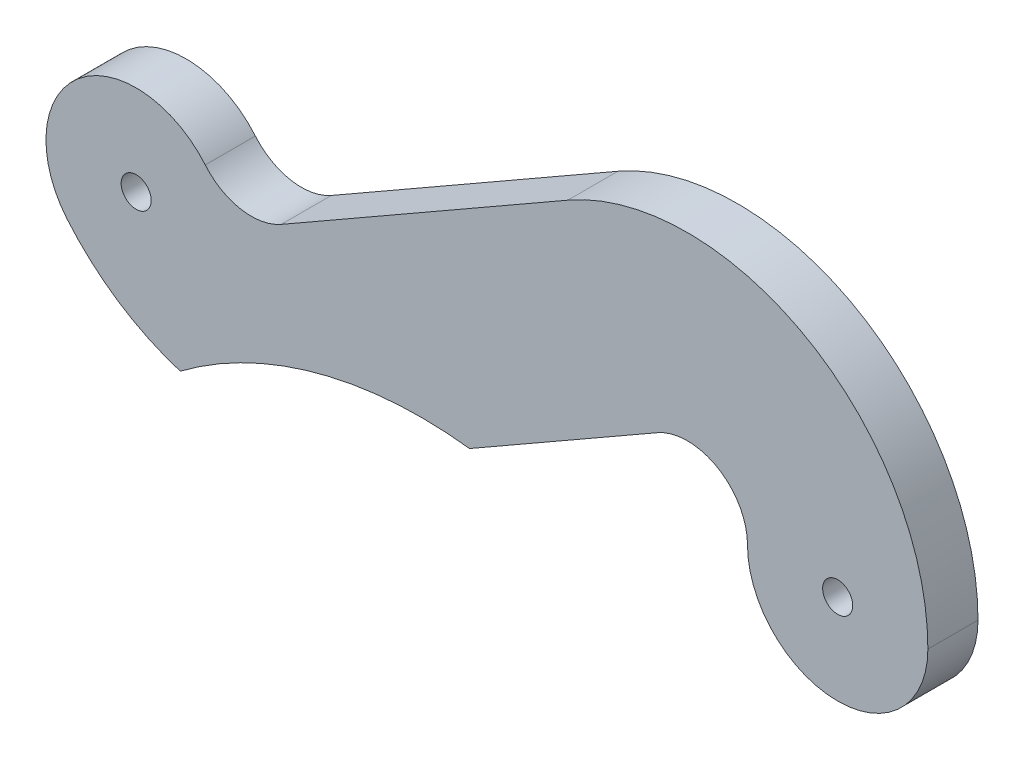
SolidWorks part; units mm, degrees
ref_plane "Plan de face" through (0, 0, 0) normal (0, 0, 1) x (1, 0, 0)
ref_plane "Plan de dessus" through (0, 0, 0) normal (0, 1, 0) x (1, 0, 0)
ref_plane "Plan de droite" through (0, 0, 0) normal (1, 0, 0) x (0, 0, -1)
sketch "Esquisse1" plane through (0, 0, 0) normal (0, 0, 1) x (1, 0, 0)
  line L0 (0, 0) -> (70, 0) construction
  line L1 (0, 0) -> (0, 15) construction
  line L2 (0, 0) -> (11.4907, 9.6418) construction
  line L3 (70, -15) -> (70, 0) construction
  line L4 (70, 0) -> (55, 0) construction
  line L5 (14.4741, 4.4361) -> (43.0662, 20.8227)
  line L6 (23.4245, -11.1809) -> (52.0166, 5.2057)
  arc A0 (11.4907, 9.6418) -> (0, 15) centre (0, 0) ccw construction
  arc A1 (16.0869, 13.4985) -> (0, 21) centre (0, 0) ccw construction
  circle A2 centre (70, 0) radius 1.5
  circle A3 centre (0, 0) radius 1.5
  arc A4 (6.8944, 5.7851) -> (0, 9) centre (0, 0) ccw construction
  arc A5 (6.8944, 5.7851) -> (16.0869, 13.4985) centre (11.4907, 9.6418) ccw construction
  arc A6 (0, 21) -> (0, 9) centre (0, 15) ccw construction
  arc A7 (55, 0) -> (70, -15) centre (70, 0) ccw construction
  arc A8 (49, 0) -> (70, -21) centre (70, 0) ccw construction
  arc A9 (61, 0) -> (70, -9) centre (70, 0) ccw construction
  arc A10 (61, 0) -> (49, 0) centre (55, 0) ccw construction
  arc A11 (70, -21) -> (70, -9) centre (70, -15) ccw construction
  arc A12 (6.8944, 5.7851) -> (-6.8944, -5.7851) centre (0, 0) ccw
  arc A13 (61, 0) -> (79, 0) centre (70, 0) ccw
  arc A14 (6.8944, 5.7851) -> (14.4741, 4.4361) centre (11.4907, 9.6418) ccw
  arc A15 (61, 0) -> (52.0166, 5.2057) centre (55, 0) ccw
  arc A16 (-6.8944, -5.7851) -> (23.4245, -11.1809) centre (11.4907, 9.6418) ccw
  arc A17 (79, 0) -> (43.0662, 20.8227) centre (55, 0) ccw
  point P6 (6.3393, 13.5946)
  point P15 (59.3934, -10.6066)
  dimension "D1" = 3
  dimension "D2" = 70
  dimension "D3" = 15
  dimension "D6" = 50
  dimension "D7" = 90
  dimension "D8" = 6
  dimension "D4" = 90
extrude "Boss.-Extru.1" add sketch "Esquisse1" along normal blind 5
sketch "Esquisse2" plane through (0, 0, 5) normal (0, 0, 1) x (1, 0, 0)
  line L1 (23.4245, -11.1809) -> (52.0166, 5.2057) construction
  arc A0 (4.4015, -13.2873) -> (33.2657, -5.5407) centre (28.4513, -45.2499) cw
  arc A1 (-6.8944, -5.7851) -> (23.4245, -11.1809) centre (11.4907, 9.6418) ccw construction
  arc A2 (4.4015, -13.2873) -> (33.2657, -5.5407) centre (13.6384, 9.9437) ccw
  dimension "D1" = 40
extrude "Enlèv. mat.-Extru.1" cut sketch "Esquisse2" against normal blind 10
